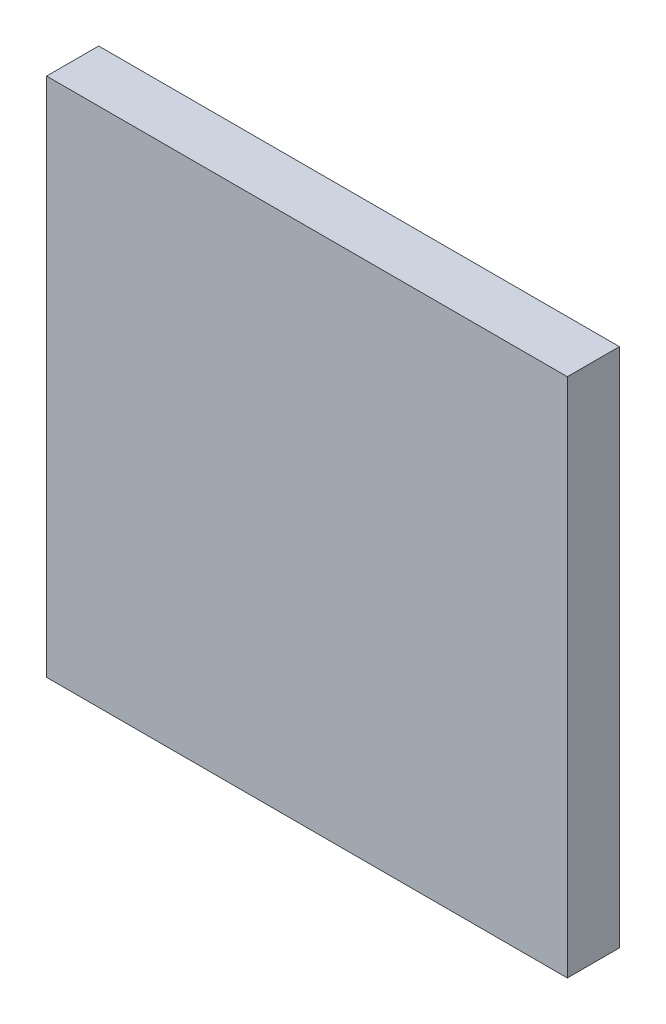
SolidWorks part; units mm, degrees
ref_plane "Plan de face" through (0, 0, 0) normal (0, 0, 1) x (1, 0, 0)
ref_plane "Plan de dessus" through (0, 0, 0) normal (0, 1, 0) x (1, 0, 0)
ref_plane "Plan de droite" through (0, 0, 0) normal (1, 0, 0) x (0, 0, -1)
sketch "Esquisse1" plane through (0, 0, 0) normal (0, 0, 1) x (1, 0, 0)
  line L1 (-5, -5) -> (5, -5)
  line L2 (-5, -5) -> (-5, 5)
  line L3 (-5, 5) -> (5, 5)
  line L4 (5, -5) -> (5, 5)
  line L5 (-5, -5) -> (5, 5) construction
  line L6 (-5, 5) -> (5, -5) construction
  point P0 (0, 0)
  dimension "D1" = 10
  dimension "D2" = 10
extrude "Extrusion1" add sketch "Esquisse1" along normal blind 1
